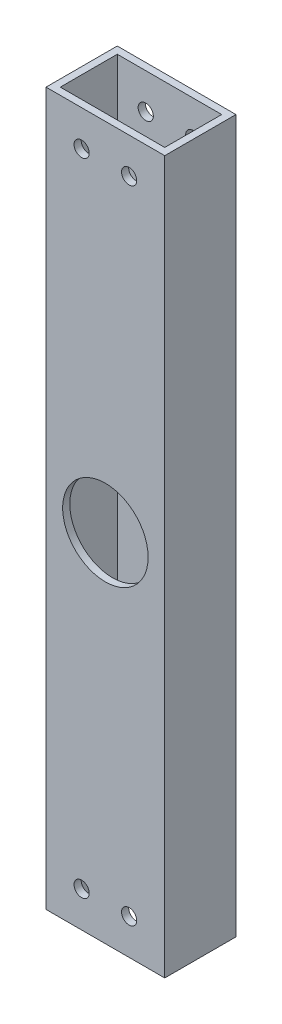
SolidWorks part; units mm, degrees
ref_plane "正面" through (0, 0, 0) normal (0, 0, 1) x (1, 0, 0)
ref_plane "平面" through (0, 0, 0) normal (0, 1, 0) x (1, 0, 0)
ref_plane "右側面" through (0, 0, 0) normal (1, 0, 0) x (0, 0, -1)
sketch "ｽｹｯﾁ1" plane through (0, 0, 0) normal (0, 1, 0) x (1, 0, 0)
  line L0 (-11, 6) -> (-11, -6)
  line L1 (-12.5, 7.5) -> (12.5, 7.5)
  line L2 (-12.5, 7.5) -> (-12.5, -7.5)
  line L3 (-12.5, -7.5) -> (12.5, -7.5)
  line L4 (12.5, 7.5) -> (12.5, -7.5)
  line L5 (-12.5, 7.5) -> (12.5, -7.5) construction
  line L6 (-12.5, -7.5) -> (12.5, 7.5) construction
  line L7 (-11, -6) -> (11, -6)
  line L8 (11, 6) -> (11, -6)
  line L9 (-11, 6) -> (11, 6)
  point P0 (0, 0)
  dimension "D1" = 15
  dimension "D2" = 25
  dimension "D3" = 1.5
extrude "ﾎﾞｽ - 押し出し1" add sketch "ｽｹｯﾁ1" along normal blind 150
sketch "ｽｹｯﾁ2" plane through (0, 0, 7.5) normal (0, 0, 1) x (1, 0, 0)
  line L1 (12.5, 150) -> (12.5, 0) construction
  line L2 (-12.5, 0) -> (12.5, 0) construction
  line L3 (-12.5, 75) -> (12.5, 75) construction
  line L4 (-12.5, 150) -> (-12.5, 0) construction
  circle A0 centre (5, 7.5) radius 1.6
  circle A2 centre (-5, 7.5) radius 1.6
  circle A3 centre (5, 142.5) radius 1.6
  circle A4 centre (-5, 142.5) radius 1.6
  circle A5 centre (0, 75) radius 9
  dimension "D1" = 7.5
  dimension "D2" = 17.5
  dimension "D3" = 7.5
  dimension "D4" = 7.5
extrude "ｶｯﾄ - 押し出し1" cut sketch "ｽｹｯﾁ2" against normal through all
